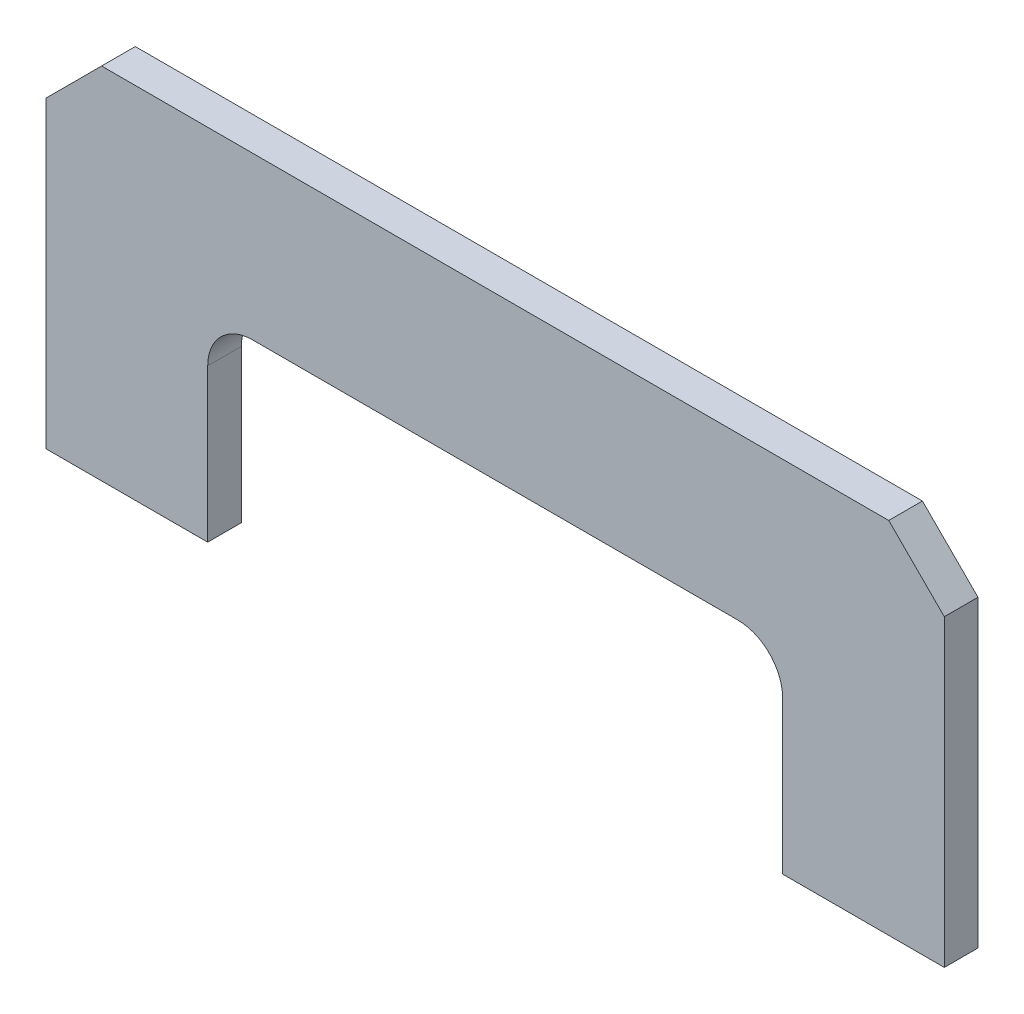
SolidWorks part; units mm, degrees
material "Alloy Steel"
ref_plane "Front Plane" through (0, 0, 0) normal (0, 0, 1) x (1, 0, 0)
ref_plane "Top Plane" through (0, 0, 0) normal (0, 1, 0) x (1, 0, 0)
ref_plane "Right Plane" through (0, 0, 0) normal (1, 0, 0) x (0, 0, -1)
sketch "Sketch1" plane through (0, 0, 0) normal (0, 0, 1) x (1, 0, 0)
  line L1 (0, 0) -> (11.43, 0)
  line L2 (0, 0) -> (0, 25.4)
  line L4 (11.43, 0) -> (11.43, 13.97)
  line L5 (52.07, 0) -> (63.5, 0)
  line L6 (52.07, 0) -> (52.07, 13.97)
  line L8 (63.5, 0) -> (63.5, 25.4)
  line L9 (11.43, 13.97) -> (52.07, 13.97)
  line L11 (0, 25.4) -> (63.5, 25.4)
  dimension "D1" = 40.64
  dimension "D3" = 63.5
  dimension "D4" = 25.4
  dimension "D5" = 11.43
extrude "Boss-Extrude1" add sketch "Sketch1" along normal blind 2.3813
fillet "Fillet1" radius 3.175 2 edges at (52.07, 13.97, 1.1906) (11.43, 13.97, 1.1906)
sketch "Sketch2" plane through (0, 0, 2.3813) normal (0, 0, 1) x (1, 0, 0)
  line L0 (0, 21.4711) -> (3.9289, 25.4)
  line L1 (0, 25.4) -> (0, 0) construction
  line L2 (63.5, 25.4) -> (0, 25.4) construction
  line L3 (59.5711, 25.4) -> (63.5, 21.4711)
  line L4 (63.5, 0) -> (63.5, 25.4) construction
  line M1 (0, 25.4) -> (0, 0)
  line M9 (63.5, 0) -> (63.5, 25.4)
  line M10 (63.5, 25.4) -> (0, 25.4)
  dimension "D1" = 45
  dimension "D2" = 45
  dimension "D3" = 5.5562
  dimension "D4" = 5.5562
extrude "Cut-Extrude1" cut sketch "Sketch2" against normal through all contours L0 M1 M10 | L3 M10 M9
scale "Scale1" [suppressed]
